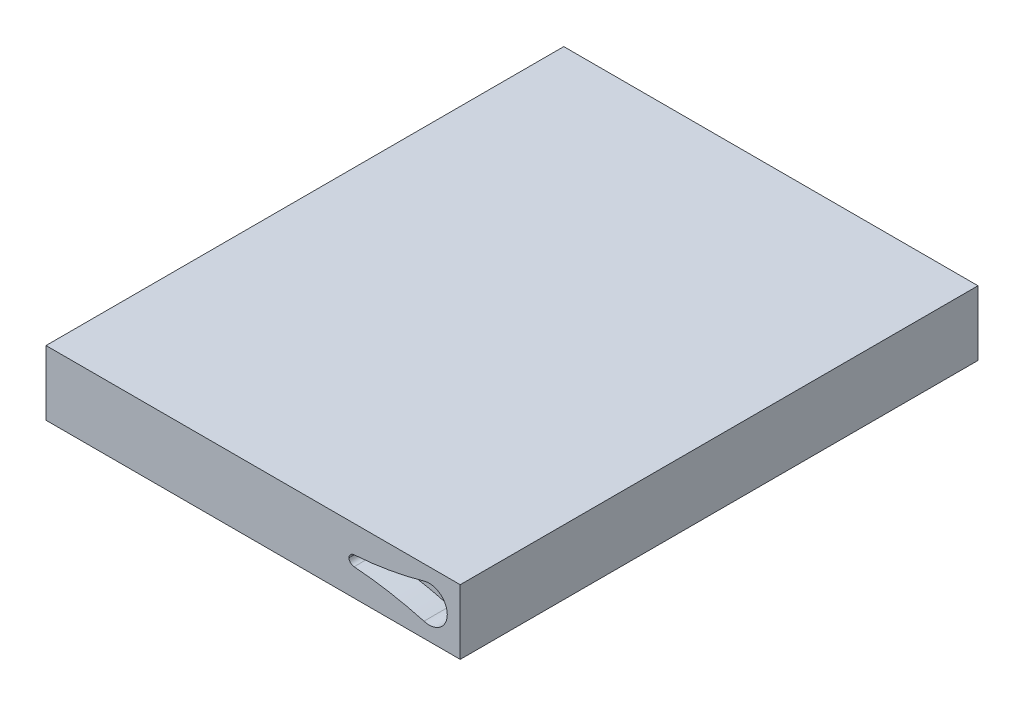
SolidWorks part; units mm, degrees
ref_plane "Front Plane" through (0, 0, 0) normal (0, 0, 1) x (1, 0, 0)
ref_plane "Top Plane" through (0, 0, 0) normal (0, 1, 0) x (1, 0, 0)
ref_plane "Right Plane" through (0, 0, 0) normal (1, 0, 0) x (0, 0, -1)
sketch "Sketch1" plane through (0, 0, 0) normal (0, 1, 0) x (1, 0, 0)
  line L1 (0, 0) -> (80, 0)
  line L2 (0, 0) -> (0, 100)
  line L3 (0, 100) -> (80, 100)
  line L4 (80, 0) -> (80, 100)
  dimension "D1" = 100
  dimension "D2" = 80
extrude "Boss-Extrude1" add sketch "Sketch1" along normal blind 12.5
sketch "Sketch2" plane through (0, 0, 0) normal (0, 0, 1) x (1, 0, 0)
  line L0 (80, 6.25) -> (74, 6.25)
  line L1 (80, 12.5) -> (80, 0) construction
  line L2 (80, 12.5) -> (73, 12.5)
  line L3 (0, 12.5) -> (80, 12.5) construction
  line L4 (73, 12.5) -> (73, 9.6041)
  line L5 (73, 9.6041) -> (73, 2.8959)
  line L6 (77.5, 6.25) -> (58.5, 6.25)
  line L7 (58.5, 6.25) -> (59.5, 6.25)
  circle A0 centre (74, 6.25) radius 3.5
  arc A1 (58.5, 6.25) -> (59.5, 7.25) centre (59.574, 6.176) cw
  arc A2 (58.5, 6.25) -> (59.5, 5.25) centre (59.5813, 6.3313) ccw
  arc A3 (59.5, 5.25) -> (73, 2.8959) centre (54.2313, -64.8501) cw
  arc A4 (59.5, 7.25) -> (73, 9.6041) centre (54.956, 73.1943) ccw
  dimension "D1" = 7
  dimension "D2" = 7
  dimension "D3" = 19
  dimension "D4" = 1
  dimension "D5" = 1
  dimension "D6" = 1
  dimension "D7" = 6
extrude "Cut-Extrude1" cut sketch "Sketch2" against normal blind 5 contours L0 A0 L5 L6 | L5 A0 L0 L6 | L6 A0 L5 | L5 A0 L6 | A2 A3 A0 L6 | A4 A1 L6 A0
sketch "Sketch5" plane through (0, 0, 0) normal (1, 0, 0) x (0, 0, -1)
  line L0 (0, 12.5) -> (114.4818, 12.5) construction
ref_plane "Plane1" through (0, 0, -100) normal (0, 0, 1) x (1, 0, 0)
sketch "Sketch6" plane through (0, 0, -100) normal (0, 0, 1) x (1, 0, 0)
  line L0 (0, 12.5) -> (7, 12.5)
  line L1 (0, 12.5) -> (80, 12.5) construction
  line L3 (20.5, 6.2474) -> (20.5, 7.2474) construction
  line L4 (0, 6.25) -> (6, 6.25)
  line L5 (0, 12.5) -> (0, 0) construction
  line L6 (2.5, 6.25) -> (21.5, 6.25)
  line L7 (21.5, 6.25) -> (20.5, 6.25)
  line L9 (7, 12.5) -> (7, 9.6041)
  line L10 (7, 9.6041) -> (7, 2.8959)
  line L11 (40, 12.5) -> (40, 0) construction
  line L12 (80, 12.5) -> (0, 12.5) construction
  line L13 (80, 0) -> (0, 0) construction
  line L14 (77.5, 6.25) -> (58.5, 6.25)
  circle A0 centre (6, 6.25) radius 3.5
  arc A1 (21.5, 6.25) -> (20.5, 5.2474) centre (20.5, 6.2474) cw
  arc A2 (21.5, 6.25) -> (20.5, 7.2474) centre (20.5, 6.2474) ccw
  arc A3 (20.5, 7.2474) -> (7, 9.6041) centre (20.5, 47.092) cw
  arc A5 (20.5, 5.2474) -> (7, 2.8959) centre (20.5, -34.6803) ccw
  arc A6 (7, 9.6041) -> (7, 2.8959) centre (6, 6.25) cw
  arc A7 (58.5, 6.25) -> (59.5, 7.2474) centre (59.5, 6.2474) cw
  arc A8 (58.5, 6.25) -> (59.5, 5.2474) centre (59.5, 6.2474) ccw
  arc A9 (59.5, 5.2474) -> (73, 2.8959) centre (59.5, -34.6803) cw
  arc A10 (59.5, 7.2474) -> (73, 9.6041) centre (59.5, 47.092) ccw
  circle A11 centre (74, 6.25) radius 3.5
  dimension "D3" = 7
  dimension "D1" = 7
  dimension "D2" = 6
  dimension "D4" = 19
  dimension "D5" = 1
  dimension "D6" = 1
  dimension "D7" = 1
extrude "Cut-Extrude4" cut sketch "Sketch6" along normal blind 5 contours A11 L14 A9 | A11 L14 A10 | L14 A11 A10 A7 | A9 A11 L14 A8 | L6
